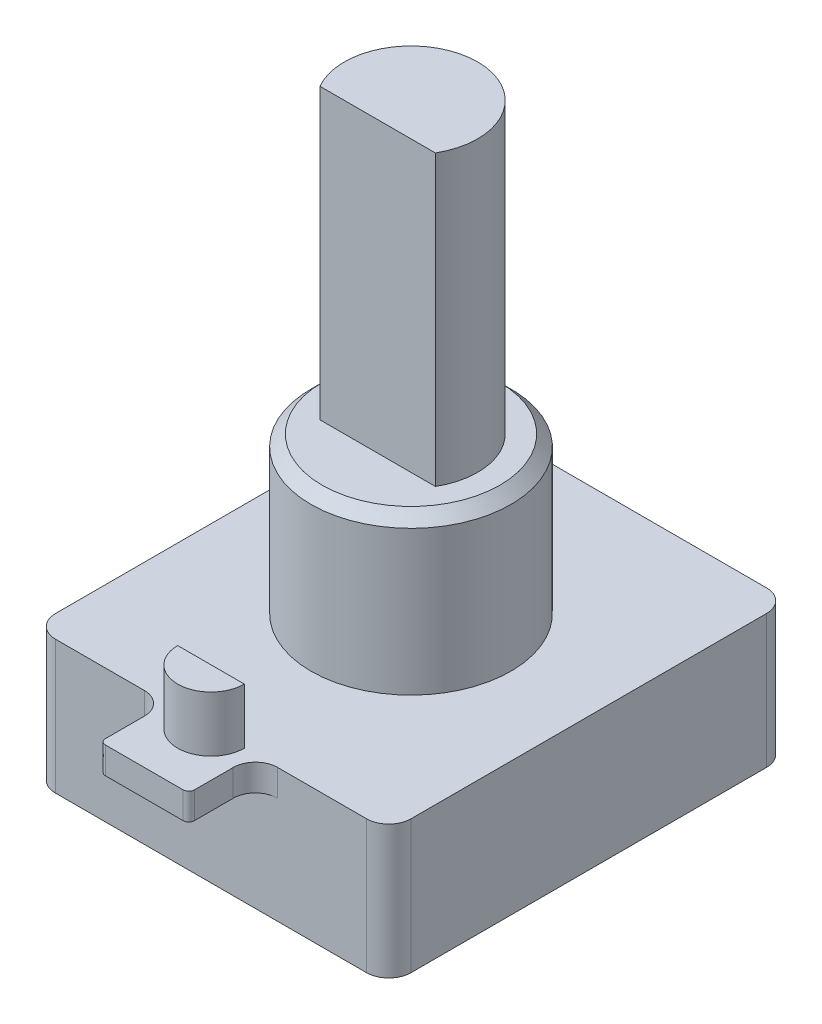
SolidWorks part; units mm, degrees
ref_plane "Спереди" through (0, 0, 0) normal (0, 0, 1) x (1, 0, 0)
ref_plane "Сверху" through (0, 0, 0) normal (0, 1, 0) x (1, 0, 0)
ref_plane "Справа" through (0, 0, 0) normal (1, 0, 0) x (0, 0, -1)
sketch "Эскиз1" plane through (0, 0, 0) normal (0, 1, 0) x (1, 0, 0)
  line L1 (-8, -9) -> (8, -9)
  line L2 (-8, -9) -> (-8, 9)
  line L3 (-8, 9) -> (8, 9)
  line L4 (8, -9) -> (8, 9)
  line L5 (-8, -9) -> (8, 9) construction
  line L6 (-8, 9) -> (8, -9) construction
  point P0 (0, 0)
  dimension "D1" = 16
  dimension "D2" = 18
extrude "Бобышка-Вытянуть1" add sketch "Эскиз1" along normal blind 6
fillet "Скругление1" radius 1 4 edges at (8, 3, -9) (-8, 3, -9) (-8, 3, 9) (8, 3, 9)
sketch "Эскиз2" plane through (0, 0, 9) normal (0, 0, 1) x (1, 0, 0)
  line L0 (-7, 6) -> (7, 6) construction
  line L1 (-2, 4.8) -> (2, 4.8)
  line L2 (-2, 4.8) -> (-2, 6)
  line L3 (-2, 6) -> (2, 6)
  line L4 (2, 4.8) -> (2, 6)
  line L5 (-2, 4.8) -> (2, 6) construction
  line L6 (-2, 6) -> (2, 4.8) construction
  point P0 (0, 5.4)
  point P5 (0, 0)
  point P6 (0, 0)
  dimension "D1" = 4
  dimension "D2" = 1.2
extrude "Бобышка-Вытянуть2" add sketch "Эскиз2" along normal blind 3
fillet "Скругление2" radius 1 2 edges at (-2, 5.4, 9) (2, 5.4, 9)
fillet "Скругление3" radius 0.25 2 edges at (2, 5.4, 12) (-2, 5.4, 12)
sketch "Эскиз3" plane through (0, 6, 0) normal (0, 1, 0) x (1, 0, 0)
  circle A0 centre (0, 0) radius 4.5
extrude "Бобышка-Вытянуть3" add sketch "Эскиз3" along normal blind 7
chamfer "Фаска1" distance 0.5 angle 45 1 edges at (0, 13, 4.5)
sketch "Эскиз4" plane through (0, 13, 0) normal (0, 1, 0) x (1, 0, 0)
  line L0 (-2.9594, 3) -> (4.1873, 3) construction
  line L1 (-2.5981, -1.5) -> (2.5981, -1.5)
  arc A0 (2.5981, -1.5) -> (-2.5981, -1.5) centre (0, 0) ccw
  point P7 (0, 0)
  point P8 (2.4784, -1.6904)
  point P9 (-2.382, -1.8238)
  dimension "D1" = 6
  dimension "D2" = 4.5
extrude "Бобышка-Вытянуть4" add sketch "Эскиз4" along normal blind 13
sketch "Эскиз5" plane through (0, 6, 0) normal (0, 1, 0) x (1, 0, 0)
  line L0 (-4.6243, -10.5) -> (4.4432, -10.5) construction
  line L1 (-11.4593, 4.5) -> (15.2081, 4.5) construction
  line L2 (-1.5, -9) -> (1.5, -9)
  arc A0 (-1.5, -9) -> (1.5, -9) centre (0, -9) ccw
  circle A1 centre (0, 0) radius 4.5 construction
  point P8 (1.2608, -8.1873)
  point P12 (-1.3626, -8.3729)
  dimension "D1" = 3
  dimension "D3" = 1.5
  dimension "D2" = 15
extrude "Бобышка-Вытянуть5" add sketch "Эскиз5" along normal blind 2.5 contours A0 L2
